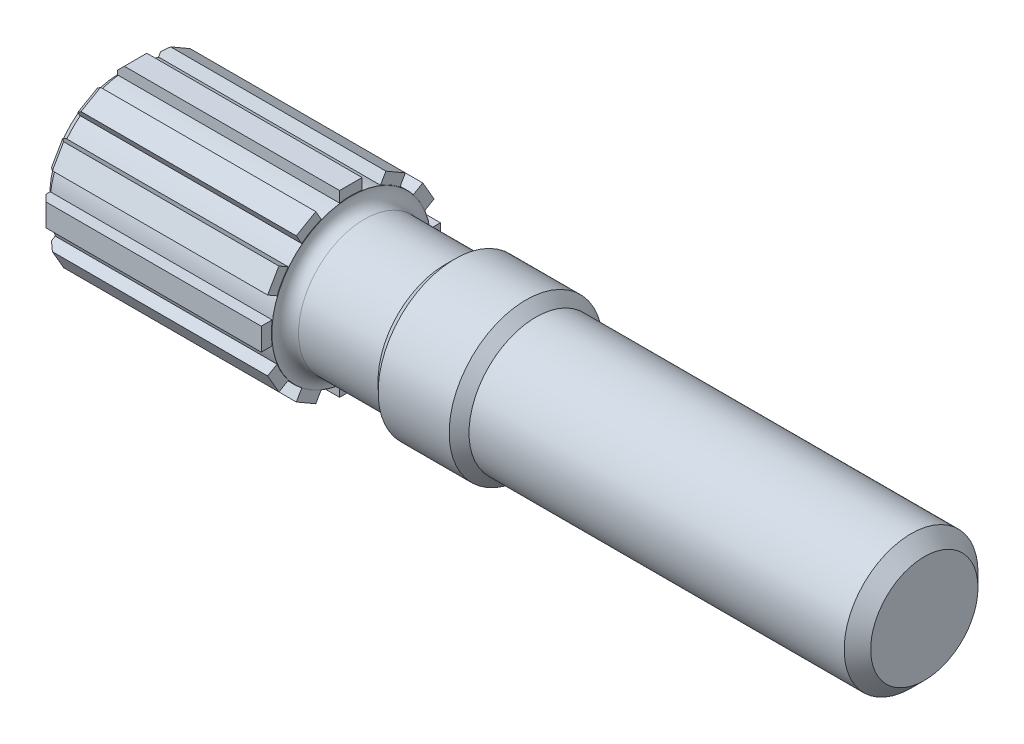
SolidWorks part; units mm, degrees
ref_plane "Front Plane" through (0, 0, 0) normal (0, 0, 1) x (1, 0, 0)
ref_plane "Top Plane" through (0, 0, 0) normal (0, 1, 0) x (1, 0, 0)
ref_plane "Right Plane" through (0, 0, 0) normal (1, 0, 0) x (0, 0, -1)
sketch "Sketch1" plane through (0, 0, 0) normal (0, 1, 0) x (1, 0, 0)
  line L0 (77.9948, 0) -> (-59.5052, 0) construction
  line L2 (-44.8637, 0) -> (76.6649, 0)
  line L3 (-44.8637, 10.5) -> (-44.8637, 0)
  line L4 (16.5246, 11.6037) -> (5.8003, 11.6037)
  line L5 (76.6649, 0) -> (76.6649, 8.1029)
  line L6 (-9.8637, 11.9623) -> (-9.8637, 12)
  line L8 (-43.3637, 12) -> (-9.8637, 12)
  line L9 (-7.8637, 9.9623) -> (4.3003, 9.9623)
  line L10 (18.0246, 10.1029) -> (74.6649, 10.1029)
  line L11 (4.3003, 9.9623) -> (4.3003, 10.1037)
  line L12 (74.6649, 10.1029) -> (76.6649, 8.1029)
  line L13 (5.8003, 11.6037) -> (4.3003, 10.1037)
  line L14 (18.0246, 10.1029) -> (18.0246, 10.1037)
  line L15 (18.0246, 10.1037) -> (16.5246, 11.6037)
  line L16 (-44.8637, 10.5) -> (-43.3637, 12)
  arc A0 (-7.8637, 9.9623) -> (-9.8637, 11.9623) centre (-7.8637, 11.9623) cw
  point P4 (76.6649, 10.1029)
  point P5 (0, 0)
  point P8 (-44.8637, 12)
  point P13 (4.3003, 11.6037)
  point P14 (-44.8637, 12)
  point P23 (18.0246, 11.6037)
  dimension "D3" = 2
  dimension "D1" = 24
  dimension "D2" = 35
revolve "Revolve1" add sketch "Sketch1" angle 360 about L0
sketch "Sketch2" plane through (-44.9219, 0, 0) normal (-1, 0, 0) x (0, 0, 1)
  line L2 (-1.6992, 13.5246) -> (1.6992, 13.5246)
  line L3 (-1.6992, 13.5246) -> (-1.6992, 11.0856)
  line L4 (-1.6992, 11.0856) -> (1.6992, 11.0856)
  line L5 (1.6992, 13.5246) -> (1.6992, 11.0856)
  point P0 (0, 13.5246)
  point P1 (0, 0)
  point P3 (0, 0)
  dimension "D1" = 3.3984
  dimension "D2" = 13.5246
extrude "Boss-Extrude1" add sketch "Sketch2" against normal blind 33.5 from offset 1.5 offset against normal yes
pattern_circular "CirPattern1" count 12 over 360 about axis through (0, 0, 0) along (1, 0, 0) of "Boss-Extrude1"
chamfer "Chamfer1" distance 1 angle 45 12 edges at (-43.4219, 11.7127, 6.7623) (-43.4219, 6.7623, 11.7127) (-43.4219, 0, 13.5246) (-43.4219, -6.7623, 11.7127) (-43.4219, -11.7127, 6.7623) (-43.4219, -13.5246, 0) (-43.4219, -11.7127, -6.7623) (-43.4219, -6.7623, -11.7127) (-43.4219, 0, -13.5246) (-43.4219, 6.7623, -11.7127) (-43.4219, 11.7127, -6.7623) (-43.4219, 13.5246, 0)
